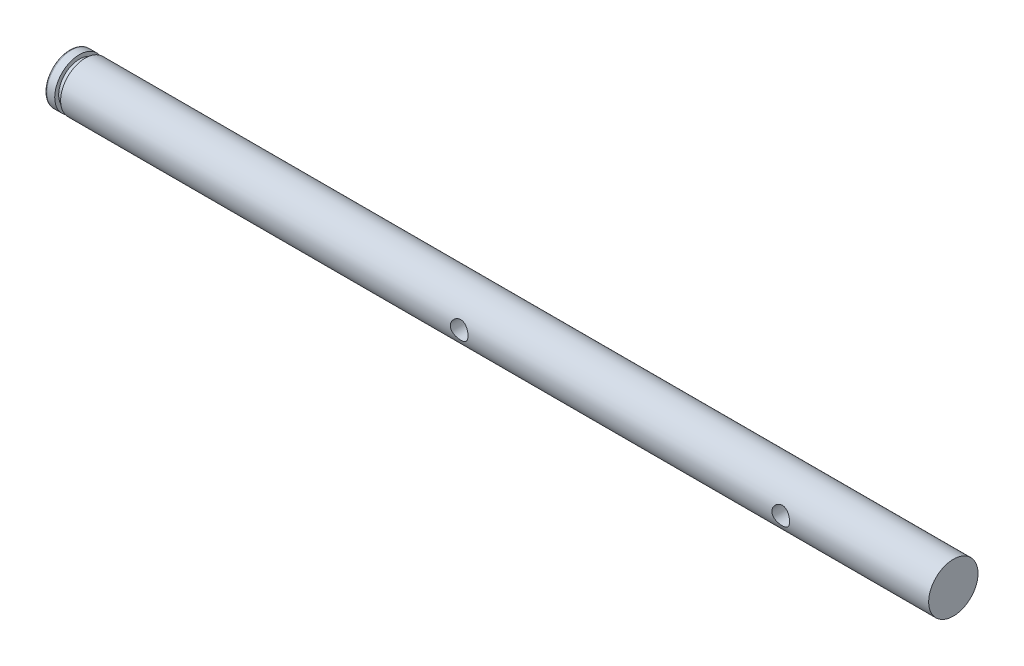
SolidWorks part; units mm, degrees
ref_plane "Front Plane" through (0, 0, 0) normal (0, 0, 1) x (1, 0, 0)
ref_plane "Top Plane" through (0, 0, 0) normal (0, 1, 0) x (1, 0, 0)
ref_plane "Right Plane" through (0, 0, 0) normal (1, 0, 0) x (0, 0, -1)
sketch "Sketch1" plane through (0, 0, 0) normal (1, 0, 0) x (0, 0, -1)
  circle A0 centre (0, 0) radius 3.175
  dimension "D1" = 6.35
extrude "Boss-Extrude1" add sketch "Sketch1" against normal blind 111.76
sketch "Sketch2" plane through (-111.76, 0, 0) normal (-1, 0, 0) x (0, 0, 1)
  circle A0 centre (0, 0) radius 2.667
  dimension "D1" = 5.334
extrude "Boss-Extrude2" add sketch "Sketch2" along normal blind 0.762
sketch "Sketch3" plane through (-112.522, 0, 0) normal (-1, 0, 0) x (0, 0, 1)
  circle A0 centre (0, 0) radius 3.175
  dimension "D1" = 6.35
extrude "Boss-Extrude3" add sketch "Sketch3" along normal blind 1.27
fillet "Fillet1" radius 0.254 1 edges at (-113.792, 0, 3.175)
sketch "Sketch4" plane through (0, 0, 0) normal (0, 0, 1) x (1, 0, 0)
  line L0 (0, -3.175) -> (0, 3.175) construction
  circle A0 centre (-60.452, 0) radius 1.143
  circle A1 centre (-19.05, 0) radius 1.143
  dimension "D1" = 2.286
  dimension "D2" = 60.452
  dimension "D3" = 19.05
extrude "Cut-Extrude1" cut sketch "Sketch4" against normal through all both and the other way through all contours A0 | A1
